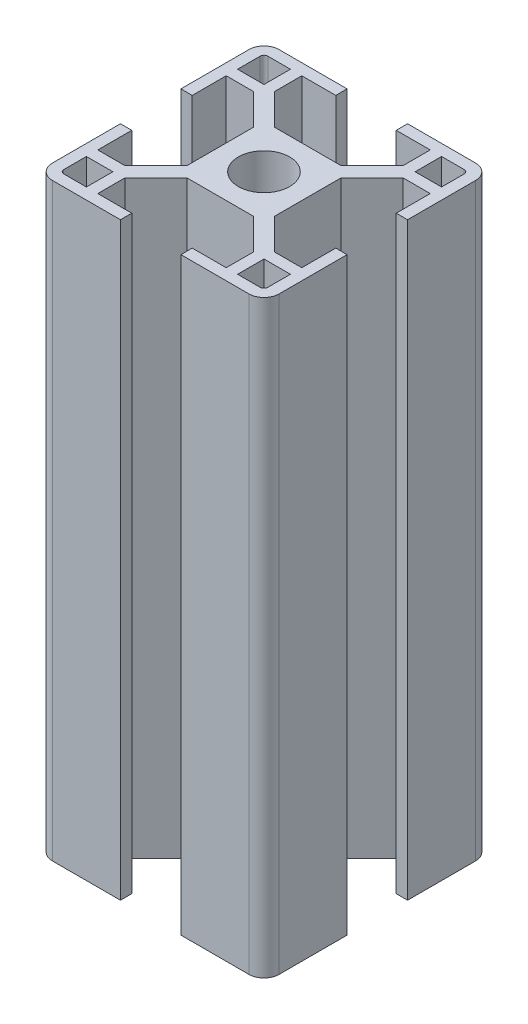
SolidWorks part; units mm, degrees
ref_plane "Płaszczyzna przednia" through (0, 0, 0) normal (0, 0, 1) x (1, 0, 0)
ref_plane "Płaszczyzna górna" through (0, 0, 0) normal (0, 1, 0) x (1, 0, 0)
ref_plane "Płaszczyzna prawa" through (0, 0, 0) normal (1, 0, 0) x (0, 0, -1)
sketch "Szkic2" plane through (0, 0, 0) normal (0, 1, 0) x (1, 0, 0)
  line L0 (10.0014, -10.0002) -> (13.5014, -10.0002)
  line L1 (10.0002, 10.0014) -> (13.5002, 10.0014)
  line L2 (10.0002, 10.0014) -> (10.0002, 13.5014)
  line L3 (10.0002, 13.5014) -> (13.0002, 13.5014)
  line L4 (13.5002, 10.0014) -> (13.5002, 13.0014)
  line L5 (10.0014, -10.0002) -> (10.0014, -13.5002)
  line L6 (10.0014, -13.5002) -> (13.0014, -13.5002)
  line L7 (13.5014, -10.0002) -> (13.5014, -13.0002)
  line L8 (-10.0002, -10.0014) -> (-10.0002, -13.5014)
  line L9 (-10.0002, -10.0014) -> (-13.5002, -10.0014)
  line L10 (-13.5002, -10.0014) -> (-13.5002, -13.0014)
  line L11 (-10.0002, -13.5014) -> (-13.0002, -13.5014)
  line L12 (-10.0014, 10.0002) -> (-13.5014, 10.0002)
  line L13 (-10.0014, 10.0002) -> (-10.0014, 13.5002)
  line L14 (-10.0014, 13.5002) -> (-13.0014, 13.5002)
  line L15 (-13.5014, 10.0002) -> (-13.5014, 13.0002)
  line L88 (15.0002, 4.0014) -> (15.0002, 13.0014)
  line L89 (13.0002, 15.0014) -> (4.0002, 15.0014)
  line L90 (4.0002, 15.0014) -> (4.0002, 13.5014)
  line L91 (4.0002, 13.5014) -> (8.5002, 13.5014)
  line L92 (8.5002, 13.5014) -> (8.5002, 9.9157)
  line L93 (8.5002, 9.9157) -> (4.386, 5.8014)
  line L94 (4.386, 5.8014) -> (-4.3856, 5.8014)
  line L95 (-4.3856, 5.8014) -> (-8.4998, 9.9157)
  line L96 (-8.4998, 9.9157) -> (-8.4998, 13.5014)
  line L97 (-8.4998, 13.5014) -> (-3.9998, 13.5014)
  line L98 (-3.9998, 13.5014) -> (-3.9998, 15.0014)
  line L99 (-3.9998, 15.0014) -> (-12.9998, 15.0014)
  line L100 (-14.9998, 13.0014) -> (-14.9998, 4.0014)
  line L101 (-14.9998, 4.0014) -> (-13.4998, 4.0014)
  line L102 (-13.4998, 4.0014) -> (-13.4998, 8.5014)
  line L103 (-13.4998, 8.5014) -> (-9.914, 8.5014)
  line L104 (-9.914, 8.5014) -> (-5.7998, 4.3872)
  line L105 (-5.7998, 4.3872) -> (-5.7998, -4.3843)
  line L106 (-5.7998, -4.3843) -> (-9.914, -8.4986)
  line L107 (-9.914, -8.4986) -> (-13.4998, -8.4986)
  line L108 (-13.4998, -8.4986) -> (-13.4998, -3.9986)
  line L109 (-13.4998, -3.9986) -> (-14.9998, -3.9986)
  line L110 (-14.9998, -3.9986) -> (-14.9998, -12.9986)
  line L111 (-12.9998, -14.9986) -> (-3.9998, -14.9986)
  line L112 (-3.9998, -14.9986) -> (-3.9998, -13.4986)
  line L113 (-3.9998, -13.4986) -> (-8.4998, -13.4986)
  line L114 (-8.4998, -13.4986) -> (-8.4998, -9.9128)
  line L115 (-8.4998, -9.9128) -> (-4.3856, -5.7986)
  line L116 (-4.3856, -5.7986) -> (4.386, -5.7986)
  line L117 (4.386, -5.7986) -> (8.5002, -9.9128)
  line L118 (8.5002, -9.9128) -> (8.5002, -13.4986)
  line L119 (8.5002, -13.4986) -> (4.0002, -13.4986)
  line L120 (4.0002, -13.4986) -> (4.0002, -14.9986)
  line L121 (4.0002, -14.9986) -> (13.0002, -14.9986)
  line L122 (15.0002, -12.9986) -> (15.0002, -3.9986)
  line L123 (15.0002, -3.9986) -> (13.5002, -3.9986)
  line L124 (13.5002, -3.9986) -> (13.5002, -8.4986)
  line L125 (13.5002, -8.4986) -> (9.9144, -8.4986)
  line L126 (9.9144, -8.4986) -> (5.8002, -4.3843)
  line L127 (5.8002, -4.3843) -> (5.8002, 4.3872)
  line L128 (5.8002, 4.3872) -> (9.9144, 8.5014)
  line L129 (9.9144, 8.5014) -> (13.5002, 8.5014)
  line L130 (13.5002, 8.5014) -> (13.5002, 4.0014)
  line L131 (13.5002, 4.0014) -> (15.0002, 4.0014)
  circle A0 centre (0, 0) radius 3.4
  arc A1 (13.0002, 13.5014) -> (13.5002, 13.0014) centre (13.0002, 13.0014) cw
  arc A2 (13.5014, -13.0002) -> (13.0014, -13.5002) centre (13.0014, -13.0002) cw
  arc A3 (-13.0002, -13.5014) -> (-13.5002, -13.0014) centre (-13.0002, -13.0014) cw
  arc A4 (-13.5014, 13.0002) -> (-13.0014, 13.5002) centre (-13.0014, 13.0002) cw
  arc A8 (15.0002, 13.0014) -> (13.0002, 15.0014) centre (13.0002, 13.0014) ccw
  arc A9 (-12.9998, 15.0014) -> (-14.9998, 13.0014) centre (-12.9998, 13.0014) ccw
  arc A10 (-14.9998, -12.9986) -> (-12.9998, -14.9986) centre (-12.9998, -12.9986) ccw
  arc A11 (13.0002, -14.9986) -> (15.0002, -12.9986) centre (13.0002, -12.9986) ccw
  point P82 (0, 0)
  dimension "D2" = 6.8
  dimension "D5" = 0.5
  dimension "D1" = 30
  dimension "D3" = 3.5
  dimension "D4" = 3.5
  dimension "D6" = 1.5
  dimension "D7" = 1.5
  dimension "D8" = 4
extrude "Dodanie-wyciągnięcie1" add sketch "Szkic2" along normal blind 78
equation "\"D4@Szkic2\"=\"D3@Szkic2\""
equation "\"D7@Szkic2\"=\"D6@Szkic2\""
